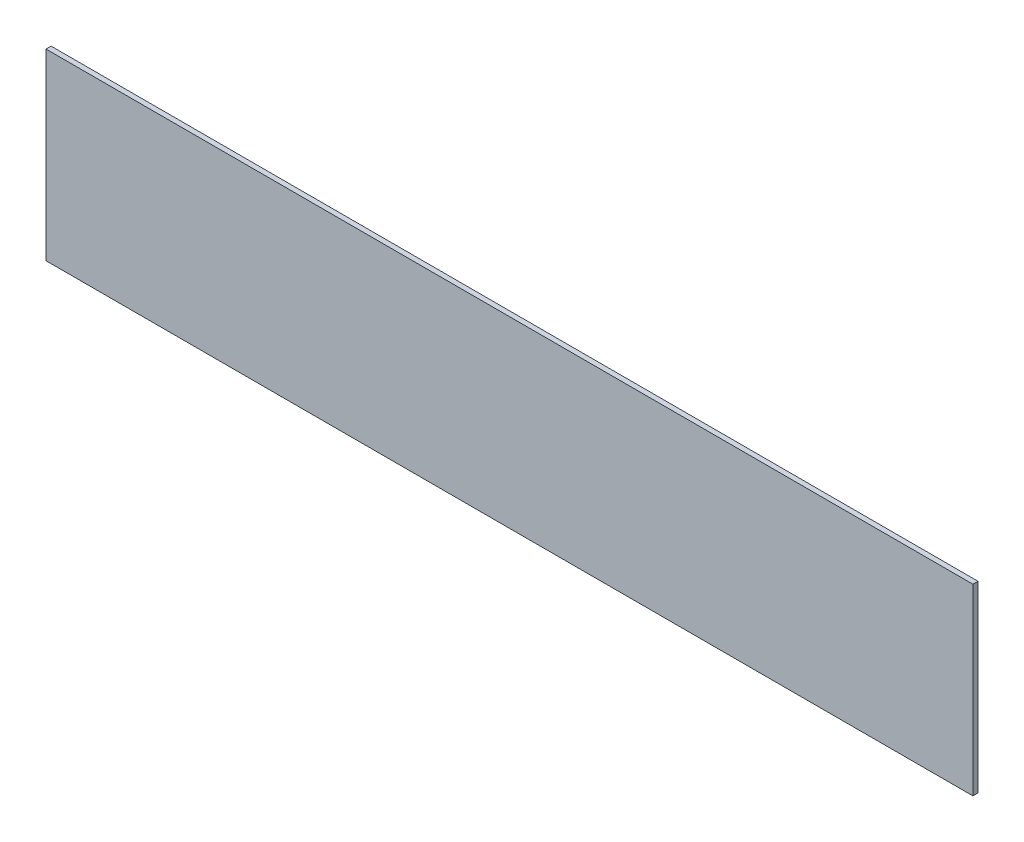
SolidWorks part; units mm, degrees
ref_plane "Front Plane" through (0, 0, 0) normal (0, 0, 1) x (1, 0, 0)
ref_plane "Top Plane" through (0, 0, 0) normal (0, 1, 0) x (1, 0, 0)
ref_plane "Right Plane" through (0, 0, 0) normal (1, 0, 0) x (0, 0, -1)
other "Configuration Table"
sketch "Sketch1" plane through (0, 0, 0) normal (0, 0, 1) x (1, 0, 0)
  line L1 (259, 1337) -> (441, 1337)
  line L2 (259, 1337) -> (259, 1373)
  line L3 (259, 1373) -> (441, 1373)
  line L4 (441, 1337) -> (441, 1373)
extrude "TOPPING_klape_kat2_kulp_cukuru_1" add sketch "Sketch1" along normal blind 1 from offset 26 separate body
